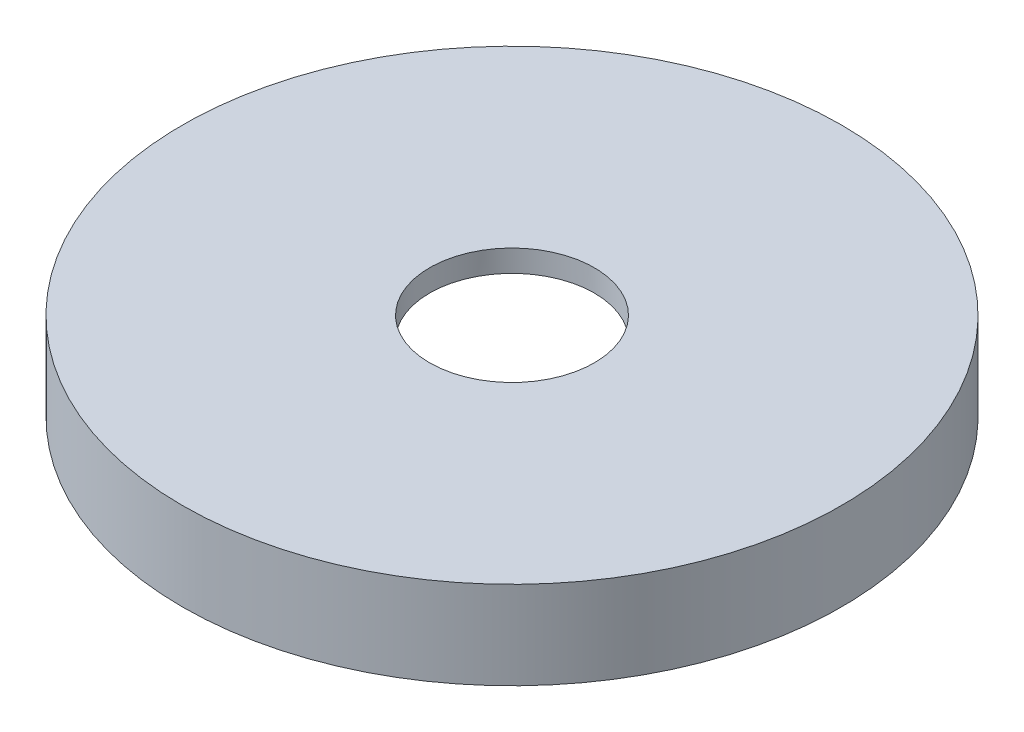
SolidWorks part; units mm, degrees
ref_plane "Plan de face" through (0, 0, 0) normal (0, 0, 1) x (1, 0, 0)
ref_plane "Plan de dessus" through (0, 0, 0) normal (0, 1, 0) x (1, 0, 0)
ref_plane "Plan de droite" through (0, 0, 0) normal (1, 0, 0) x (0, 0, -1)
sketch "Esquisse1" plane through (0, 0, 0) normal (0, 1, 0) x (1, 0, 0)
  circle A0 centre (0, 0) radius 30
  dimension "D1" = 60
extrude "Boss.-Extru.1" add sketch "Esquisse1" along normal blind 8
sketch "Esquisse2" plane through (0, 0, 0) normal (0, -1, 0) x (1, 0, 0)
  circle A0 centre (0, 0) radius 17.5
  dimension "D1" = 35
extrude "Enlèv. mat.-Extru.1" cut sketch "Esquisse2" against normal blind 6
sketch "Esquisse3" plane through (0, 8, 0) normal (0, 1, 0) x (1, 0, 0)
  circle A0 centre (0, 0) radius 7.5
  dimension "D1" = 15
extrude "Enlèv. mat.-Extru.2" cut sketch "Esquisse3" against normal through all
